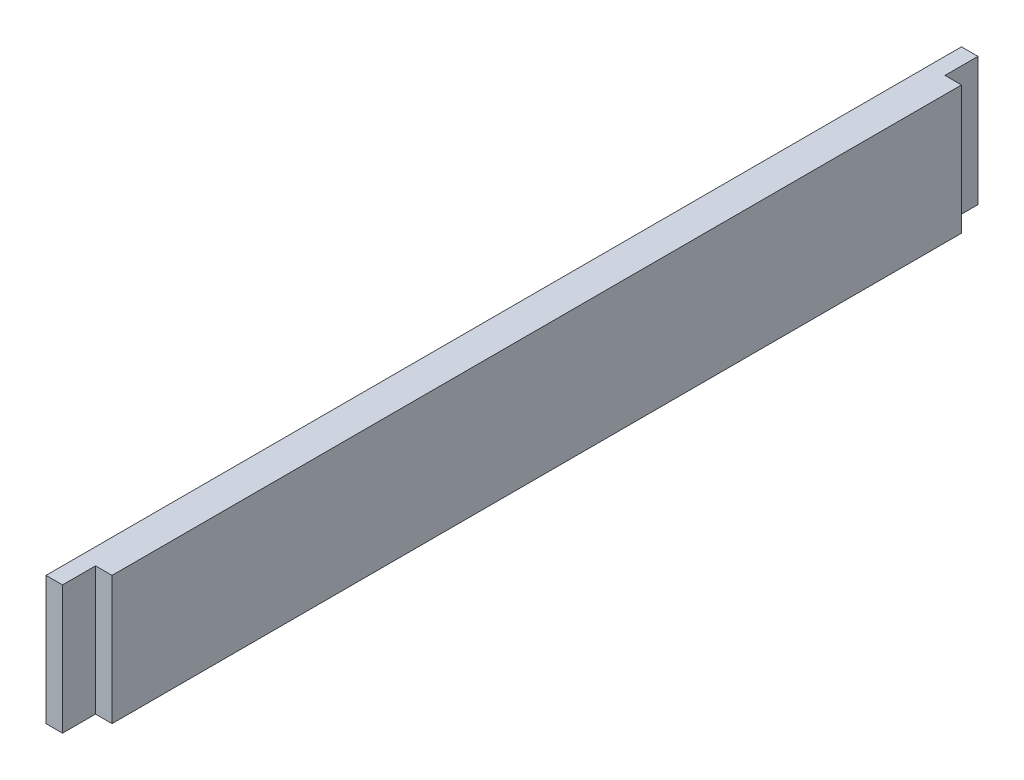
SolidWorks part; units mm, degrees
ref_plane "Front Plane" through (0, 0, 0) normal (0, 0, 1) x (1, 0, 0)
ref_plane "Top Plane" through (0, 0, 0) normal (0, 1, 0) x (1, 0, 0)
ref_plane "Right Plane" through (0, 0, 0) normal (1, 0, 0) x (0, 0, -1)
sketch "Sketch1" plane through (0, 0, 0) normal (1, 0, 0) x (0, 0, -1)
  line L1 (0, 0) -> (499, 0)
  line L2 (0, 0) -> (0, 70)
  line L3 (0, 70) -> (499, 70)
  line L4 (499, 0) -> (499, 70)
  dimension "D1" = 499
  dimension "D2" = 70
extrude "Boss-Extrude1" add sketch "Sketch1" along normal blind 18
sketch "Sketch2" plane through (18, 0, 0) normal (1, 0, 0) x (0, 0, -1)
  line L0 (249.5, 70) -> (249.5, 0) construction
  line L1 (499, 70) -> (0, 70) construction
  line L2 (0, 0) -> (499, 0) construction
  line L3 (499, 0) -> (481, 0)
  line L4 (0, 70) -> (18, 70)
  line L5 (0, 70) -> (0, 0)
  line L6 (0, 0) -> (18, 0)
  line L7 (18, 70) -> (18, 0)
  line L8 (481, 70) -> (481, 0)
  line L9 (499, 70) -> (481, 70)
  line L10 (499, 70) -> (499, 0)
  dimension "D1" = 18
extrude "Cut-Extrude1" cut sketch "Sketch2" against normal blind 9
